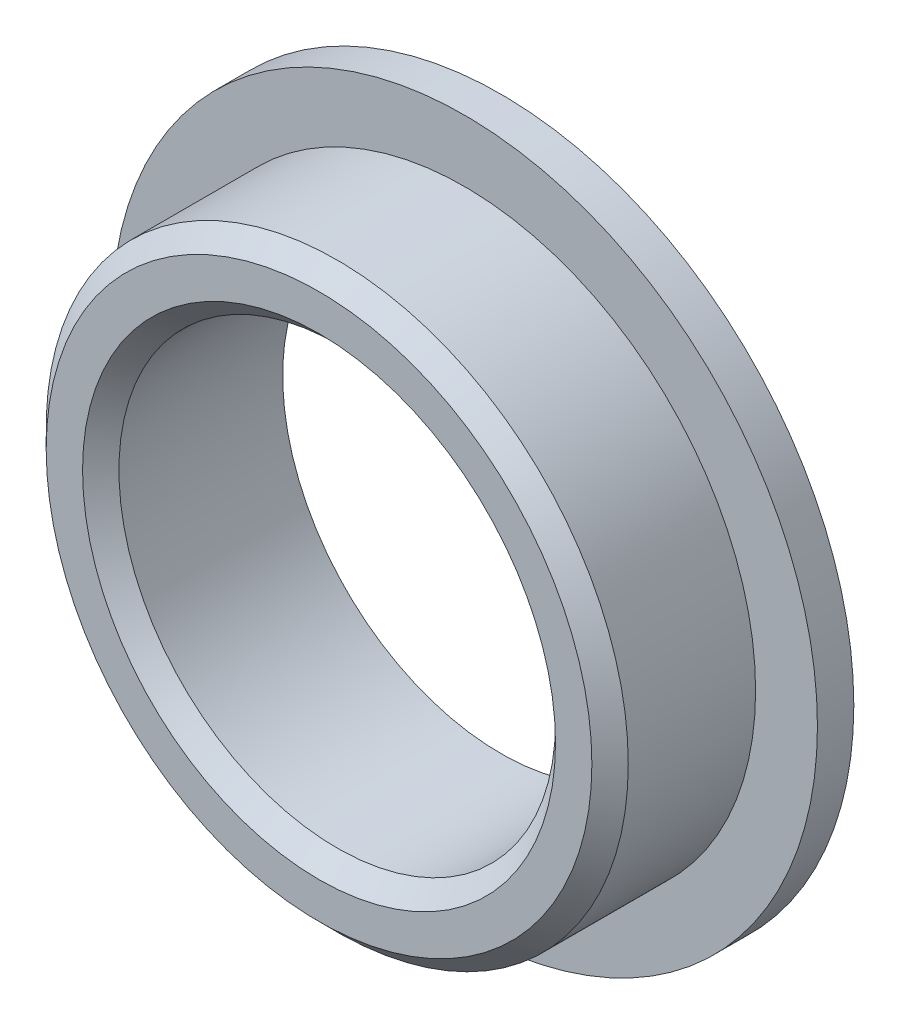
SolidWorks part; units mm, degrees
ref_plane "前基準面" through (0, 0, 0) normal (0, 0, 1) x (1, 0, 0)
ref_plane "上基準面" through (0, 0, 0) normal (0, 1, 0) x (1, 0, 0)
ref_plane "右基準面" through (0, 0, 0) normal (1, 0, 0) x (0, 0, -1)
sketch "草圖1" plane through (0, 0, 0) normal (0, 0, 1) x (1, 0, 0)
  circle A0 centre (0, 0) radius 4.85
  dimension "D1" = 9.7
extrude "伸長1" add sketch "草圖1" along normal blind 0.5
sketch "草圖2" plane through (0, 0, 0.5) normal (0, 0, 1) x (1, 0, 0)
  circle A0 centre (0, 0) radius 4
  dimension "D1" = 8
extrude "伸長2" add sketch "草圖2" along normal blind 2
sketch "草圖3" plane through (0, 0, 2.5) normal (0, 0, 1) x (1, 0, 0)
  circle A0 centre (0, 0) radius 3
  dimension "D1" = 6
extrude "伸長3" cut sketch "草圖3" against normal through all
chamfer "導角1" distance 0.25 angle 45 2 edges at (4, 0, 2.5) (3, 0, 2.5)
